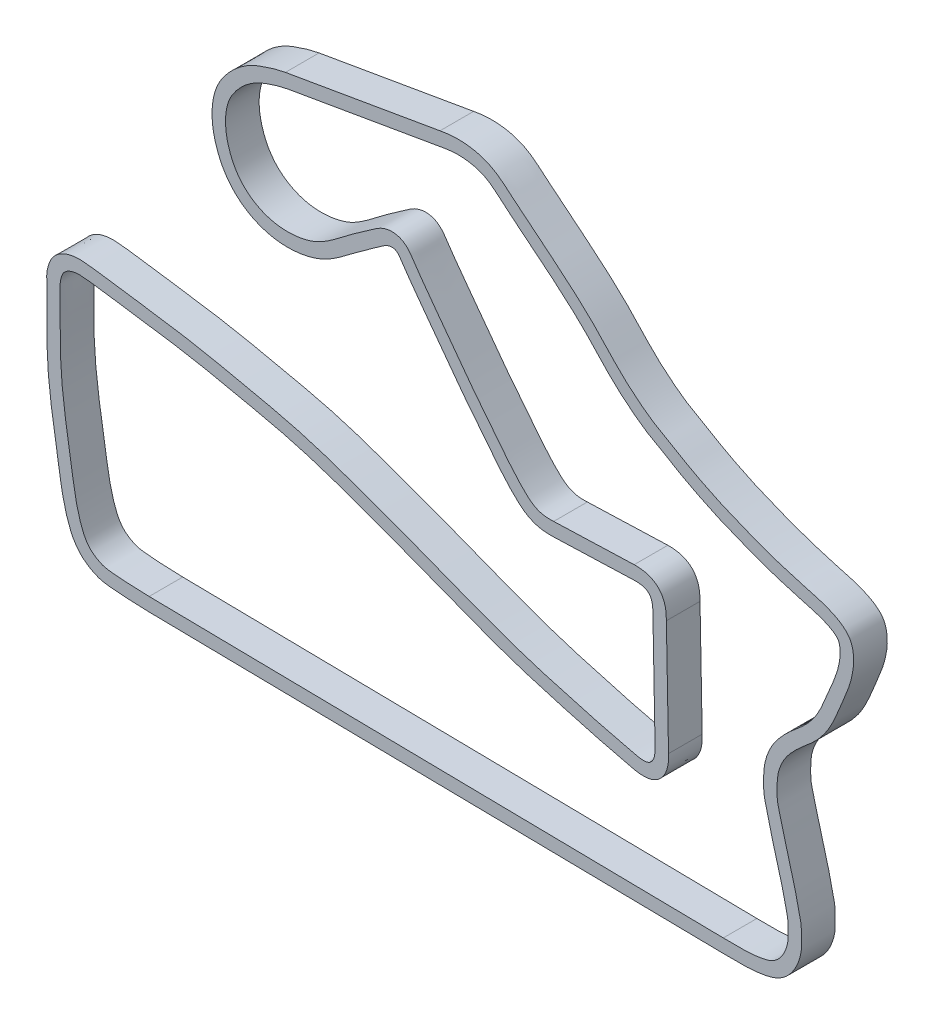
SolidWorks part; units mm, degrees
ref_plane "Front Plane" through (0, 0, 0) normal (0, 0, 1) x (1, 0, 0)
ref_plane "Top Plane" through (0, 0, 0) normal (0, 1, 0) x (1, 0, 0)
ref_plane "Right Plane" through (0, 0, 0) normal (1, 0, 0) x (0, 0, -1)
sketch "Sketch1" plane through (0, 0, 0) normal (0, 0, 1) x (1, 0, 0)
  line L0 (270.1667, 590.5) -> (1350.8333, 590.5) construction
  line L1 (255.8333, 545) -> (1279.1667, 545) construction
  line L6 (510.9481, 0) -> (77.5689, 6.5134)
  line L7 (457.9874, 195.7967) -> (459.6225, 109.7871)
  line L8 (383.4434, 208.2555) -> (444.2084, 210.3603)
  line L9 (180.596, 410.6964) -> (297.281, 430.8472)
  line L10 (511.1007, 10.1589) -> (77.7215, 16.6722)
  line L11 (468.1456, 195.9898) -> (469.7806, 109.9803)
  line L12 (383.0917, 218.4094) -> (443.8566, 220.5142)
  line L13 (182.325, 400.6846) -> (299.01, 420.8354)
  spline S0 degree 3 poles (77.5689, 6.5134) (69.0307, 6.6417) (55.964, 7.3696) (40.619, 8.9627) (32.5204, 13.0622) (22.3405, 20.6321) (13.3729, 40.9958) (9.6473, 68.1326) (4.5181, 98.5669) (0.8882, 127.3455) (0.2433, 155.8131) (0.7964, 176.5961) (0.2316, 189.683) (1.818, 195.7723) (3.9694, 201.1113) (8.4451, 206.0517) (15.427, 209.8082) (25.1874, 211.34) (48.2413, 208.2345) (77.1015, 204.0879) (114.2309, 198.4755) (150.5205, 190.5538) (190.2492, 182.1946) (246.071, 163.2951) (294.7616, 144.4879) (340.3552, 126.6466) (368.9495, 116.9946) (398.233, 108.8251) (423.4831, 101.8918) (439.2658, 98.3191) (447.2879, 96.1866) (451.5862, 95.9429) (456.0073, 96.7172) (459.7105, 101.9674) (459.6736, 107.0962) (459.6225, 109.7871) knots 0 0 0 0 0.037554 0.051675 0.063413 0.074522 0.103524 0.151002 0.188457 0.230817 0.270761 0.305807 0.31698 0.324431 0.331626 0.340566 0.351322 0.363771 0.380669 0.446973 0.484528 0.535661 0.600415 0.652007 0.778825 0.816085 0.854228 0.903418 0.941675 0.962299 0.970371 0.975802 0.980082 0.988237 1 1 1 1
  spline S1 degree 3 poles (457.9874, 195.7967) (457.9675, 196.8436) (457.8917, 198.8962) (457.6226, 201.8274) (456.8414, 204.6719) (455.2136, 207.4909) (452.2877, 209.3244) (448.5039, 210.2333) (445.8, 210.4154) (444.2084, 210.3603) knots 0 0 0 0 0.133759 0.259768 0.373044 0.506548 0.662787 0.79459 1 1 1 1
  spline S2 degree 3 poles (383.4434, 208.2555) (380.6542, 208.1589) (375.2808, 208.1637) (368.0453, 209.9571) (362.1701, 212.9838) (357.6843, 216.3901) (348.1132, 225.3474) (338.0133, 237.9923) (324.8053, 254.6028) (312.247, 270.6602) (298.5457, 289.4425) (284.5902, 308.2244) (274.5276, 321.9638) (268.5939, 330.5487) (266.1555, 334.3627) (263.5933, 336.4979) (260.4201, 336.8587) (256.3991, 335.7197) (250.5539, 331.3619) (242.3074, 325.8029) (227.8646, 315.2426) (213.9525, 303.8095) (192.0001, 296.9082) (171.0815, 296.3605) (150.239, 305.1756) (135.8713, 318.9173) (126.9433, 337.2914) (124.0322, 357.5943) (127.9543, 376.1912) (138.0333, 390.5213) (151.2765, 401.5624) (166.6865, 407.312) (176.222, 409.941) (180.596, 410.6964) knots 0 0 0 0 0.018811 0.03554 0.049384 0.06273 0.073096 0.137027 0.170538 0.215176 0.273365 0.32607 0.371729 0.387281 0.395895 0.401988 0.408846 0.416254 0.42951 0.457057 0.483027 0.549403 0.574968 0.635951 0.684859 0.722401 0.766603 0.819027 0.856948 0.890594 0.934458 0.969957 1 1 1 1
  spline S3 degree 3 poles (297.281, 430.8472) (300.0344, 431.3227) (306.6035, 432.3463) (316.9162, 432.2456) (328.4633, 430.1661) (340.2734, 424.936) (354.8488, 411.9093) (375.4042, 395.5753) (397.7312, 377.2183) (418.1623, 357.9542) (432.0293, 341.8468) (447.3254, 328.8219) (459.1844, 319.831) (471.659, 313.5145) (480.1945, 308.2968) (487.5261, 303.8726) (495.8408, 299.726) (506.7624, 294.1955) (531.0878, 283.9348) (559.5951, 273.3622) (587.8327, 266.7986) (600.7994, 260.1661) (607.0555, 253.8348) (609.5616, 245.877) (609.6731, 236.0219) (606.6778, 222.0949) (600.2657, 207.7716) (594.8836, 194.2955) (588.6395, 182.6353) (579.7815, 171.9777) (569.5721, 164.2319) (562.5667, 157.0656) (558.1309, 151.8487) (554.8513, 145.8001) (551.9154, 137.9703) (551.5676, 129.1233) (551.7421, 119.1577) (554.1754, 111.3693) (556.8012, 100.2313) (560.7578, 85.1341) (565.5863, 68.7671) (568.2357, 55.9485) (570.1574, 47.9204) (570.0434, 40.3596) (570.4682, 32.055) (568.4463, 23.7564) (565.0741, 16.3973) (559.9836, 9.5541) (552.489, 3.8807) (543.0931, 1.411) (529.1901, -0.4412) (518.5957, -0.1149) (510.9481, 0) knots 0 0 0 0 0.012275 0.029125 0.045009 0.063546 0.084923 0.130314 0.179056 0.211691 0.253526 0.272049 0.299844 0.318569 0.333312 0.343766 0.356146 0.374083 0.397503 0.472003 0.507371 0.524214 0.535353 0.545336 0.55997 0.578223 0.607408 0.628665 0.641923 0.665345 0.688776 0.697982 0.709328 0.718687 0.728065 0.745775 0.757063 0.771668 0.781284 0.807363 0.840162 0.85611 0.864893 0.876245 0.889154 0.901242 0.913299 0.924502 0.938412 0.953596 0.966529 1 1 1 1
  spline S4 degree 1 poles (77.7215, 16.6722) (469.7806, 109.9803) knots 0 0 1 1 construction
  spline S5 degree 1 poles (468.1456, 195.9898) (443.8566, 220.5142) knots 0 0 1 1 construction
  spline S6 degree 1 poles (383.0917, 218.4094) (182.325, 400.6846) knots 0 0 1 1 construction
  spline S7 degree 1 poles (299.01, 420.8354) (511.1007, 10.1589) knots 0 0 1 1 construction
  spline S8 degree 3 poles (77.7215, 16.6722) (76.8543, 16.6852) (75.1348, 16.7191) (71.5775, 16.8205) (67.0203, 17.0071) (61.4248, 17.3228) (56.7146, 17.657) (52.9732, 17.9657) (49.1951, 18.2965) (46.0409, 18.6707) (43.8865, 19.178) (42.8257, 19.5133) (41.7009, 19.9354) (40.2227, 20.6134) (38.3362, 21.6689) (36.4255, 22.8975) (34.2223, 24.5479) (32.1589, 26.5712) (29.8694, 29.8599) (27.8382, 33.921) (26.0679, 38.6026) (24.528, 43.6219) (23.2387, 48.6994) (21.768, 55.6428) (20.5769, 62.8185) (19.449, 70.2321) (18.2747, 77.7822) (16.762, 87.1213) (14.4271, 101.9495) (12.4667, 116.6337) (11.2496, 131.189) (10.7555, 142.1849) (10.6146, 151.4283) (10.632, 158.8353) (10.6911, 164.4589) (10.7511, 170.1627) (10.7663, 174.9842) (10.734, 178.8905) (10.6918, 181.3415) (10.6388, 183.3362) (10.5865, 185.1672) (10.5719, 186.7547) (10.6282, 188.086) (10.706, 188.9493) (10.8196, 189.705) (11.0572, 190.8508) (11.4308, 192.1527) (11.8935, 193.4864) (12.2173, 194.293) (12.535, 194.9602) (12.8079, 195.4387) (13.1315, 195.9114) (13.6642, 196.5695) (14.4989, 197.3921) (16.1086, 198.5869) (18.0649, 199.5324) (20.3062, 200.1641) (22.1694, 200.4911) (24.1605, 200.6588) (26.9682, 200.6741) (30.1468, 200.401) (33.6707, 199.9427) (37.4393, 199.4247) (42.1097, 198.7828) (47.7228, 197.9998) (55.1942, 196.9469) (64.5261, 195.6113) (75.7138, 193.9783) (86.92, 192.3223) (98.0458, 190.6229) (109.0381, 188.782) (123.6194, 185.9985) (138.325, 182.832) (153.1621, 179.6541) (167.8447, 176.4622) (182.3086, 173.0435) (196.4291, 169.0449) (210.5531, 164.6003) (228.2602, 158.4487) (249.4964, 150.7568) (270.6508, 142.8199) (288.2538, 136.0581) (302.3372, 130.5923) (312.8883, 126.4765) (323.5018, 122.3374) (334.242, 118.2602) (345.1246, 114.3558) (356.0633, 110.6737) (367.0808, 107.2027) (378.1014, 103.9447) (389.1122, 100.8284) (398.2402, 98.3013) (405.5704, 96.2829) (411.0984, 94.7845) (416.657, 93.3148) (422.2434, 91.8868) (426.9429, 90.7445) (430.6401, 89.8692) (433.3862, 89.2186) (436.0968, 88.5681) (438.3464, 88.0142) (440.0938, 87.5702) (441.5404, 87.1995) (443.1466, 86.8133) (444.9124, 86.4441) (446.8542, 86.1311) (448.9451, 85.9225) (451.1993, 85.8713) (453.1184, 85.98) (454.9626, 86.2412) (456.5066, 86.5829) (458.1942, 87.1223) (460.0447, 87.9747) (461.6793, 89.0092) (463.5759, 90.539) (465.4421, 92.6222) (467.0564, 95.1805) (468.2122, 97.7463) (468.9884, 100.2618) (469.4529, 102.6165) (469.6976, 104.7868) (469.7953, 106.7552) (469.8051, 108.2116) (469.7936, 109.2703) (469.7852, 109.7385) (469.7806, 109.9803) knots 0 0 0 0 0.003906 0.007812 0.015625 0.023438 0.03125 0.035156 0.039062 0.046875 0.050781 0.052734 0.054688 0.058594 0.0625 0.066406 0.070312 0.078125 0.085938 0.09375 0.101562 0.109375 0.117188 0.125 0.140625 0.148438 0.15625 0.171875 0.1875 0.21875 0.234375 0.25 0.265625 0.273438 0.28125 0.289062 0.296875 0.300781 0.304688 0.306641 0.308594 0.3125 0.314453 0.316406 0.318359 0.320312 0.324219 0.326172 0.328125 0.330078 0.332031 0.333984 0.335938 0.339844 0.34375 0.351562 0.355469 0.359375 0.363281 0.367188 0.375 0.378906 0.382812 0.390625 0.398438 0.40625 0.421875 0.4375 0.453125 0.46875 0.484375 0.5 0.53125 0.546875 0.5625 0.59375 0.609375 0.625 0.65625 0.6875 0.71875 0.75 0.765625 0.78125 0.796875 0.8125 0.828125 0.84375 0.859375 0.875 0.890625 0.90625 0.914062 0.921875 0.929688 0.9375 0.945312 0.949219 0.953125 0.957031 0.960938 0.962891 0.964844 0.966797 0.96875 0.970703 0.972656 0.974609 0.976562 0.977539 0.978516 0.979492 0.980469 0.981445 0.982422 0.984375 0.986328 0.988281 0.990234 0.992188 0.994141 0.996094 0.998047 0.999023 1 1 1 1
  spline S9 degree 3 poles (468.1456, 195.9898) (468.1241, 197.1174) (468.0654, 198.7409) (467.891, 201.171) (467.6183, 203.3672) (467.0891, 205.8194) (466.234, 208.3757) (465.1487, 210.6123) (463.9503, 212.4449) (462.8527, 213.8219) (461.5612, 215.1249) (459.8013, 216.5683) (457.5372, 217.9581) (454.7971, 219.1021) (452.2749, 219.7825) (450.1563, 220.1638) (447.3675, 220.5026) (445.2584, 220.5627) (443.8566, 220.5142) knots 0 0 0 0 0.125 0.1875 0.25 0.3125 0.375 0.4375 0.46875 0.5 0.53125 0.5625 0.625 0.6875 0.75 0.8125 0.875 1 1 1 1
  spline S10 degree 3 poles (383.0917, 218.4094) (382.5745, 218.3915) (381.5231, 218.3631) (379.554, 218.3553) (377.2698, 218.4549) (374.8989, 218.786) (372.5833, 219.3734) (370.4515, 220.1871) (367.5953, 221.6675) (364.8041, 223.7054) (361.9035, 226.347) (358.8357, 229.3695) (355.1462, 233.3155) (350.794, 238.3767) (346.4906, 243.662) (342.1367, 249.1355) (336.3316, 256.4327) (329.1226, 265.5513) (320.6817, 276.4882) (313.8018, 285.7804) (308.2776, 293.2999) (304.1064, 298.9644) (299.9335, 304.6054) (295.7674, 310.2341) (292.3048, 314.9212) (289.5508, 318.664) (287.4985, 321.4673) (285.4617, 324.2691) (283.4429, 327.0719) (281.447, 329.8751) (279.798, 332.2206) (278.5167, 334.0714) (277.7344, 335.2192) (277.1198, 336.135) (276.6676, 336.8153) (276.2124, 337.5117) (275.4222, 338.7019) (274.3501, 340.1922) (272.8659, 341.85) (271.4585, 343.1692) (269.9484, 344.2836) (268.502, 345.1117) (266.8512, 345.8729) (264.8262, 346.4865) (262.5562, 346.8203) (260.4559, 346.8601) (257.8484, 346.6198) (254.9278, 345.884) (251.9959, 344.6195) (249.6202, 343.2372) (248.04, 342.1539) (246.9636, 341.3811) (246.0322, 340.7055) (244.9087, 339.903) (243.5172, 338.9229) (242.1128, 337.9442) (240.214, 336.6286) (237.8007, 334.9612) (234.8443, 332.885) (231.9182, 330.7784) (229.0136, 328.6419) (225.1469, 325.7349) (220.484, 322.1359) (215.1049, 318.1453) (209.8528, 314.6731) (205.5492, 312.3557) (202.0954, 310.8959) (198.4512, 309.6184) (193.6111, 308.3765) (185.6608, 307.1782) (177.6823, 307.2585) (170.0574, 308.6856) (162.664, 311.0421) (154.1837, 315.6236) (147.2536, 322.2075) (142.9528, 328.3895) (139.3514, 335.2881) (136.1917, 344.9556) (135.1374, 354.7615) (135.6882, 362.5287) (136.6343, 367.1121) (137.7625, 370.518) (139.1186, 373.684) (141.4139, 377.5744) (145.0814, 382.1769) (149.3071, 386.4404) (153.0988, 389.475) (156.2879, 391.5747) (159.5369, 393.4203) (163.1395, 395.039) (167.0518, 396.4976) (170.1372, 397.5337) (173.3032, 398.5204) (176.3798, 399.389) (179.4116, 400.1298) (181.3418, 400.5148) (182.325, 400.6846) knots 0 0 0 0 0.003906 0.007812 0.015625 0.023438 0.03125 0.039062 0.046875 0.0625 0.070312 0.078125 0.09375 0.109375 0.125 0.140625 0.15625 0.1875 0.21875 0.25 0.265625 0.28125 0.296875 0.3125 0.328125 0.335938 0.34375 0.351562 0.359375 0.367188 0.375 0.378906 0.382812 0.384766 0.386719 0.388672 0.390625 0.394531 0.396484 0.398438 0.400391 0.401367 0.402344 0.404297 0.40625 0.408203 0.410156 0.414062 0.417969 0.421875 0.425781 0.427734 0.429688 0.433594 0.4375 0.441406 0.445312 0.453125 0.460938 0.46875 0.476562 0.484375 0.5 0.515625 0.53125 0.546875 0.554688 0.5625 0.578125 0.59375 0.625 0.640625 0.65625 0.6875 0.71875 0.734375 0.75 0.78125 0.8125 0.828125 0.84375 0.851562 0.859375 0.875 0.890625 0.90625 0.921875 0.929688 0.9375 0.953125 0.960938 0.96875 0.976562 0.984375 0.992188 1 1 1 1
  spline S11 degree 3 poles (299.01, 420.8354) (299.8339, 420.9777) (301.5079, 421.2576) (304.67, 421.7174) (308.347, 422.0612) (312.8364, 422.0799) (317.3725, 421.7265) (321.7451, 421.0138) (325.8669, 419.9167) (329.8226, 418.3811) (332.8898, 416.7678) (335.1789, 415.2819) (337.5521, 413.5578) (340.021, 411.5299) (342.6331, 409.2783) (345.3926, 406.8911) (348.8769, 403.9424) (353.0568, 400.4766) (358.6342, 395.9237) (365.5847, 390.3337) (373.8298, 383.6737) (381.9671, 376.9631) (389.9423, 370.1639) (397.7054, 363.2287) (405.2086, 356.1154) (412.2969, 348.7939) (419.5293, 340.9062) (425.9599, 334.2114) (431.5659, 328.9754) (435.8398, 325.2733) (440.1183, 321.7512) (444.522, 318.2703) (449.143, 314.8593) (453.1774, 312.1461) (456.5724, 310.0695) (459.932, 308.1466) (463.1515, 306.4137) (466.1903, 304.7613) (469.0612, 303.1471) (472.7319, 300.9601) (476.5144, 298.6465) (479.7163, 296.7348) (482.2496, 295.2843) (484.8231, 293.9031) (488.1564, 292.1952) (492.0983, 290.2264) (496.944, 287.7939) (501.9718, 285.3724) (507.0578, 283.0853) (512.1161, 280.9254) (517.1338, 278.8565) (527.1753, 274.7961) (539.0662, 270.2723) (552.9268, 265.6102) (561.712, 262.9443) (568.8336, 261.001) (575.6772, 259.192) (583.6478, 256.8866) (590.8106, 253.9507) (594.5835, 251.5533) (596.3718, 250.064) (597.1845, 249.2114) (597.6532, 248.6062) (597.9073, 248.218) (598.1151, 247.8336) (598.4203, 247.1449) (598.779, 246.0333) (599.2344, 243.7585) (599.4391, 240.65) (599.1417, 236.4168) (598.3908, 232.0693) (597.2348, 227.6506) (595.7224, 223.1643) (593.912, 218.5359) (592.2308, 214.5437) (590.8332, 211.2543) (589.4181, 207.8802) (587.7383, 203.8071) (585.7335, 199.1705) (583.6437, 194.8258) (581.3994, 190.8132) (578.909, 187.1239) (576.061, 183.5776) (573.4536, 180.8119) (571.234, 178.7166) (568.8093, 176.5638) (565.4775, 173.7598) (561.8597, 170.6415) (558.9224, 167.8469) (556.8321, 165.7147) (554.844, 163.5745) (552.8106, 161.2484) (550.7859, 158.6896) (548.8243, 155.815) (547.1374, 152.8703) (545.6936, 149.9247) (544.4083, 146.8685) (543.2856, 143.5698) (542.4349, 140.0454) (541.9225, 136.6811) (541.6374, 133.4454) (541.5338, 130.883) (541.4983, 128.9066) (541.4846, 127.0133) (541.4956, 124.5413) (541.6194, 121.8553) (541.8364, 119.604) (542.1608, 117.2546) (542.7152, 114.5308) (543.4691, 111.5852) (544.2132, 108.9224) (544.8398, 106.5871) (545.4489, 104.1135) (546.0728, 101.5146) (546.725, 98.8586) (547.6076, 95.3452) (548.745, 90.9579) (550.1551, 85.7141) (551.6102, 80.4917) (553.0555, 75.3663) (554.4481, 70.3152) (555.7529, 65.3216) (556.7156, 61.2382) (557.4657, 57.8331) (558.0354, 55.2223) (558.528, 52.9947) (558.9409, 51.1934) (559.3074, 49.5799) (559.5886, 48.1694) (559.7474, 47.0539) (559.8607, 45.8675) (559.9363, 44.0806) (559.9505, 41.9644) (559.9776, 40.0237) (560.0207, 38.1904) (560.0644, 36.1224) (560.0285, 33.9786) (559.8777, 32.2634) (559.5567, 30.4513) (559.0711, 28.5701) (558.4237, 26.6218) (557.4134, 24.1151) (555.8767, 21.1804) (554.0257, 18.6238) (552.4004, 16.8855) (551.0839, 15.7083) (549.698, 14.6853) (548.2858, 13.8425) (546.8326, 13.1692) (544.5192, 12.3417) (541.7246, 11.6728) (538.6289, 11.1198) (535.5392, 10.6716) (531.6038, 10.2845) (526.7265, 10.0571) (521.6834, 10.005) (517.3464, 10.0549) (513.8061, 10.1149) (511.9995, 10.1453) (511.1007, 10.1589) knots 0 0 0 0 0.003906 0.007812 0.015625 0.023438 0.03125 0.039062 0.046875 0.054688 0.0625 0.066406 0.070312 0.078125 0.082031 0.085938 0.09375 0.101562 0.109375 0.125 0.140625 0.15625 0.171875 0.1875 0.203125 0.21875 0.234375 0.25 0.257812 0.265625 0.273438 0.28125 0.289062 0.296875 0.300781 0.304688 0.3125 0.316406 0.320312 0.328125 0.335938 0.339844 0.34375 0.347656 0.351562 0.359375 0.367188 0.375 0.382812 0.390625 0.398438 0.40625 0.4375 0.453125 0.46875 0.476562 0.484375 0.5 0.515625 0.523438 0.527344 0.53125 0.533203 0.535156 0.537109 0.539062 0.542969 0.546875 0.554688 0.5625 0.570312 0.578125 0.585938 0.59375 0.601562 0.605469 0.609375 0.617188 0.625 0.632812 0.640625 0.648438 0.65625 0.664062 0.667969 0.671875 0.679688 0.6875 0.691406 0.695312 0.699219 0.703125 0.707031 0.710938 0.714844 0.71875 0.722656 0.726562 0.730469 0.734375 0.738281 0.742188 0.744141 0.746094 0.75 0.753906 0.755859 0.757812 0.761719 0.765625 0.769531 0.773438 0.777344 0.78125 0.785156 0.789062 0.796875 0.804688 0.8125 0.820312 0.828125 0.835938 0.84375 0.847656 0.851562 0.855469 0.857422 0.859375 0.863281 0.865234 0.867188 0.871094 0.875 0.876953 0.878906 0.882812 0.886719 0.890625 0.894531 0.898438 0.902344 0.90625 0.914062 0.921875 0.925781 0.929688 0.933594 0.9375 0.941406 0.945312 0.953125 0.957031 0.960938 0.96875 0.976562 0.984375 0.992188 0.996094 1 1 1 1
  point P13 (0, 0)
  point P15 (0, 0)
  dimension "D1" = 10.16
extrude "Boss-Extrude1" add sketch "Sketch1" along normal blind 25.4
